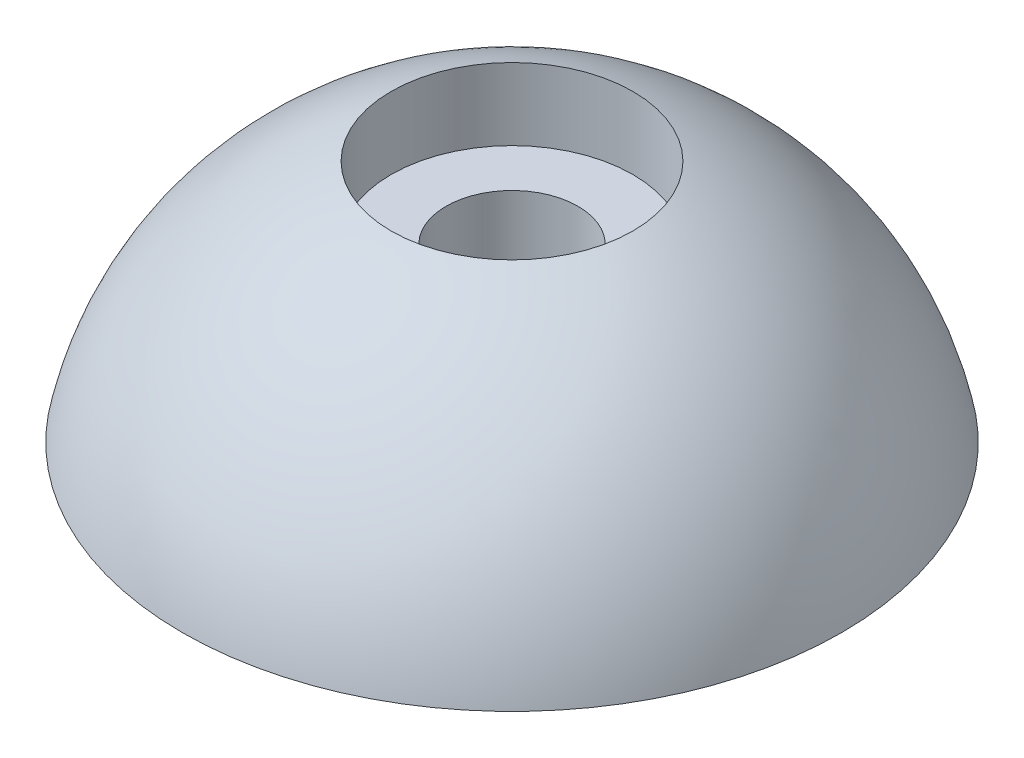
SolidWorks part; units mm, degrees
ref_plane "Front Plane" through (0, 0, 0) normal (0, 0, 1) x (1, 0, 0)
ref_plane "Top Plane" through (0, 0, 0) normal (0, 1, 0) x (1, 0, 0)
ref_plane "Right Plane" through (0, 0, 0) normal (1, 0, 0) x (0, 0, -1)
sketch "Sketch1" plane through (0, 0, 0) normal (0, 0, 1) x (1, 0, 0)
  line L0 (0, 0) -> (0, 6) construction
  line L1 (0, 0) -> (7.5, 0)
  line L2 (0, 0) -> (0, 6)
  arc A0 (7.5, 0) -> (0, 6) centre (0.1512, -1.4985) ccw
  dimension "D3" = 7.5
  dimension "D1" = 6
  dimension "D2" = 7.5
revolve "Revolve1" add sketch "Sketch1" angle 360 about L0
sketch "Sketch2" plane through (0, 0, 0) normal (0, -1, 0) x (1, 0, 0)
  circle A0 centre (0, 0) radius 1.5
  dimension "D1" = 3
extrude "Cut-Extrude1" cut sketch "Sketch2" against normal through all
ref_plane "Plane1" through (0, 6, 0) normal (0, -1, 0) x (-1, 0, 0)
sketch "Sketch4" plane through (0, 6, 0) normal (0, -1, 0) x (-1, 0, 0)
  circle A0 centre (0, 0) radius 2.75
  dimension "D1" = 5.5
extrude "Cut-Extrude2" cut sketch "Sketch4" along normal blind 2.1
